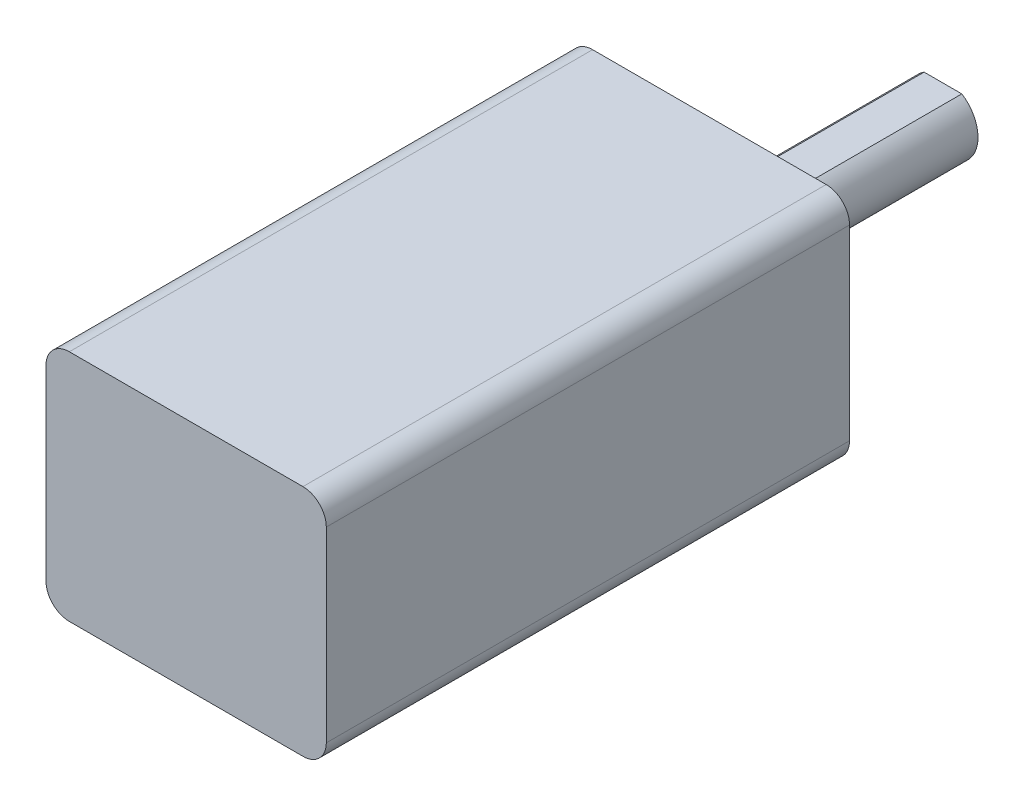
SolidWorks part; units mm, degrees
ref_plane "正面" through (0, 0, 0) normal (0, 0, 1) x (1, 0, 0)
ref_plane "平面" through (0, 0, 0) normal (0, 1, 0) x (1, 0, 0)
ref_plane "右側面" through (0, 0, 0) normal (1, 0, 0) x (0, 0, -1)
sketch "ｽｹｯﾁ1" plane through (0, 0, 0) normal (0, 0, 1) x (1, 0, 0)
  line L1 (-6, -5) -> (6, -5)
  line L2 (-6, -5) -> (-6, 5)
  line L3 (-6, 5) -> (6, 5)
  line L4 (6, -5) -> (6, 5)
  line L5 (-6, -5) -> (6, 5) construction
  line L6 (-6, 5) -> (6, -5) construction
  point P0 (0, 0)
extrude "ﾎﾞｽ - 押し出し1" add sketch "ｽｹｯﾁ1" along normal blind 22.4 contours L4 L3 L2 L1
sketch "ｽｹｯﾁ2" plane through (0, 0, 0) normal (0, 0, 1) x (1, 0, 0)
  circle A0 centre (0, 0) radius 1.5
extrude "ﾎﾞｽ - 押し出し2" add sketch "ｽｹｯﾁ2" against normal blind 10
fillet "ﾌｨﾚｯﾄ1" radius 1 1 edges at (-6, 5, 11.2)
fillet "ﾌｨﾚｯﾄ2" radius 1 3 edges at (-6, -5, 11.2) (6, -5, 11.2) (6, 5, 11.2)
sketch "ｽｹｯﾁ3" plane through (0, 0, 0) normal (0, 0, 1) x (1, 0, 0)
  line L0 (0, 1.5) -> (-1.5725, 1.5)
  line L1 (0, -5.5) -> (0, 5.5) construction
  line L2 (-1.5725, 1.5) -> (-1.5725, 1.2643)
  line L3 (-1.5725, 1.2643) -> (1.8241, 1.2643)
  line L4 (1.8241, 1.2643) -> (1.8241, 1.5)
  line L5 (1.8241, 1.5) -> (0, 1.5)
  circle A0 centre (0, 0) radius 1.5 construction
extrude "ｶｯﾄ - 押し出し1" cut sketch "ｽｹｯﾁ3" against normal blind 10
